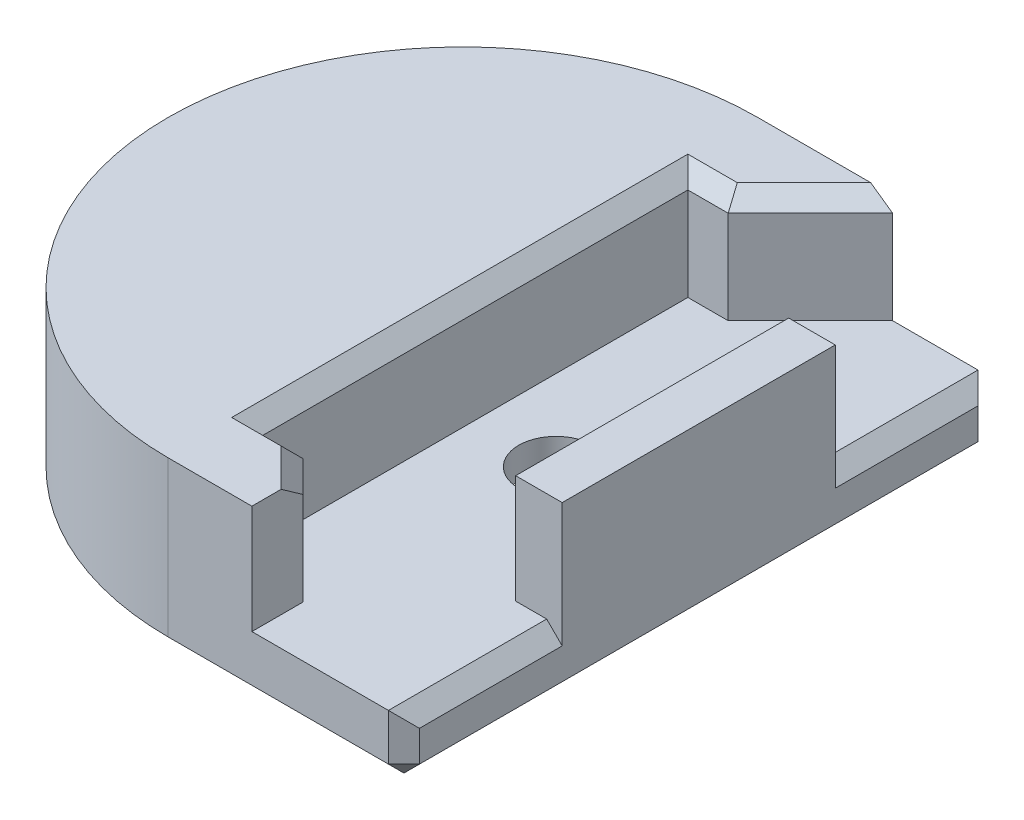
SolidWorks part; units mm, degrees
ref_plane "Front" through (0, 0, 0) normal (0, 0, 1) x (1, 0, 0)
ref_plane "Top" through (0, 0, 0) normal (0, 1, 0) x (1, 0, 0)
ref_plane "Right" through (0, 0, 0) normal (1, 0, 0) x (0, 0, -1)
sketch "Sketch1" plane through (0, 0, 0) normal (0, 1, 0) x (1, 0, 0)
  line L0 (0, 0) -> (-50000, 0) construction
  line L1 (4.6, -9.5) -> (4.6, 9.5)
  line L2 (4.6, 9.5) -> (-3, 9.5)
  line L3 (4.6, -9.5) -> (-3, -9.5)
  line L4 (13.5, 0) -> (13.5, 50000) construction
  circle A0 centre (0, 0) radius 1.2
  arc A1 (-3, -9.5) -> (-3, 9.5) centre (-3, 0) cw
  point P8 (4.6, 0)
  point P13 (-12.5, 0)
  dimension "D1" = 2.4
  dimension "D2" = 19
  dimension "D3" = 4.6
  dimension "D5" = 8.9
extrude "Boss-Extrude1" add sketch "Sketch1" along normal blind 2
sketch "Sketch2" plane through (0, 2, 0) normal (0, 1, 0) x (1, 0, 0)
  line L0 (2.6, 4.4) -> (2.6, -4.4)
  line L1 (2.6, -4.4) -> (4.6, -4.4)
  line L2 (4.6, -9.5) -> (4.6, 9.5) construction
  line L3 (4.6, -4.4) -> (4.6, 4.4)
  line L4 (4.6, 4.4) -> (2.6, 4.4)
  line L5 (200000, 0) -> (-250000, 0) construction
  line L6 (-2.6, 6.85) -> (-2.6, -6.85)
  line L7 (-2.6, -6.85) -> (-1.3, -6.85)
  line L8 (-1.3, -6.85) -> (1.35, -9.5)
  line L9 (-50, 0) -> (50, 0) construction
  line L10 (-1.3, 6.85) -> (1.35, 9.5)
  line L11 (-2.6, 6.85) -> (-1.3, 6.85)
  line L12 (-3, 9.5) -> (1.35, 9.5)
  line L13 (4.6, 9.5) -> (-3, 9.5) construction
  line L14 (4.6, -9.5) -> (-3, -9.5) construction
  line L15 (1.35, -9.5) -> (-3, -9.5)
  line L16 (-0.3, -7.85) -> (-0.3, -9.5)
  arc A2 (-3, -9.5) -> (-3, 9.5) centre (-3, 0) cw
  arc A3 (-3, 9.5) -> (-3, -9.5) centre (-3, 0) ccw construction
  point P5 (2.6, 0)
  point P11 (-2.6, 0)
  arc M7 (-3, 9.5) -> (-3, -9.5) centre (-3, 0) ccw
  line M9 (4.6, -9.5) -> (4.6, 9.5)
  dimension "D7" = 45
  dimension "D8" = 1
  dimension "D1" = 8.8
  dimension "D2" = 2
  dimension "D3" = 13.7
  dimension "D4" = 5.2
  dimension "D5" = 45
  dimension "D6" = 1.3
extrude "Boss-Extrude2" add sketch "Sketch2" along normal blind 3.5 contours L6 L11 L10 L8 L7 M7 | L4 L0 L1 M9
sketch "Sketch3" plane through (0, 0, 0) normal (0, -1, 0) x (1, 0, 0)
  line L0 (200000, 0) -> (-250000, 0) construction
  line L1 (-2.3094, 0) -> (-1.1547, -2)
  line L2 (-1.1547, -2) -> (1.1547, -2)
  line L3 (1.1547, -2) -> (2.3094, 0)
  line L4 (2.3094, 0) -> (1.1547, 2)
  line L5 (1.1547, 2) -> (-1.1547, 2)
  line L6 (-1.1547, 2) -> (-2.3094, 0)
  circle A0 centre (0, 0) radius 2 construction
  dimension "D1" = 4
extrude "Cut-Extrude1" cut sketch "Sketch3" against normal blind 1
chamfer "Chamfer1" distance 0.5 angle 45 22 edges at (-0.8, 5.5, 7.35) (-1.95, 5.5, 6.85) (-2.6, 5.5, 0) (-1.95, 5.5, -6.85) (0.025, 5.5, -8.175) (2.6, 3.75, -4.4) (2.6, 3.75, 4.4) (2.6, 5.5, 0) (0.8, 0, -9.5) (0.8, 0, 9.5) (-12.5, 0, 0) (4.6, 0, 0) (-1.7321, 0, -1) (0, 0, -2) (1.7321, 0, -1) (1.7321, 0, 1) (0, 0, 2) (-1.7321, 0, 1) (4.6, 1, 9.5) (4.6, 1, -9.5) (4.6, 2, 6.95) (4.6, 2, -6.95)
equation "\"d\" = 26mm"
equation "\"D4@Sketch1\"=\"d\""
